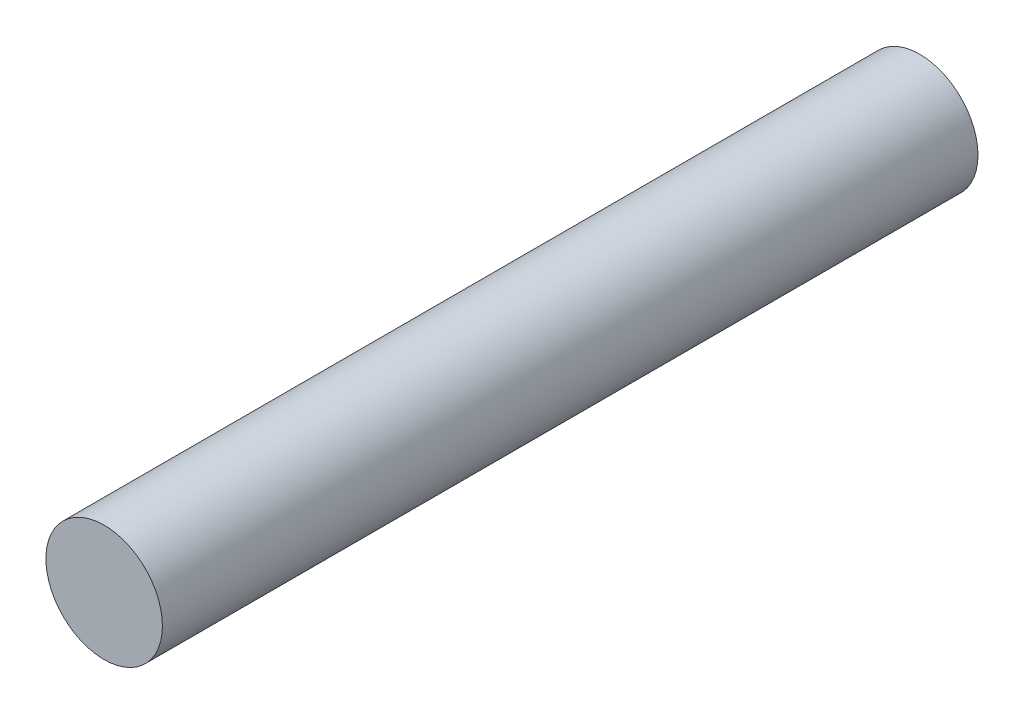
SolidWorks part; units mm, degrees
ref_plane "前视基准面" through (0, 0, 0) normal (0, 0, 1) x (1, 0, 0)
ref_plane "上视基准面" through (0, 0, 0) normal (0, 1, 0) x (1, 0, 0)
ref_plane "右视基准面" through (0, 0, 0) normal (1, 0, 0) x (0, 0, -1)
other "Configuration Table"
sketch "Sketch1" plane through (0, 0, 0) normal (0, 0, 1) x (1, 0, 0)
  circle A0 centre (0, 0) radius 2.5
  dimension "D1" = 5
extrude "Boss-Extrude1" add sketch "Sketch1" along normal mid plane 35
